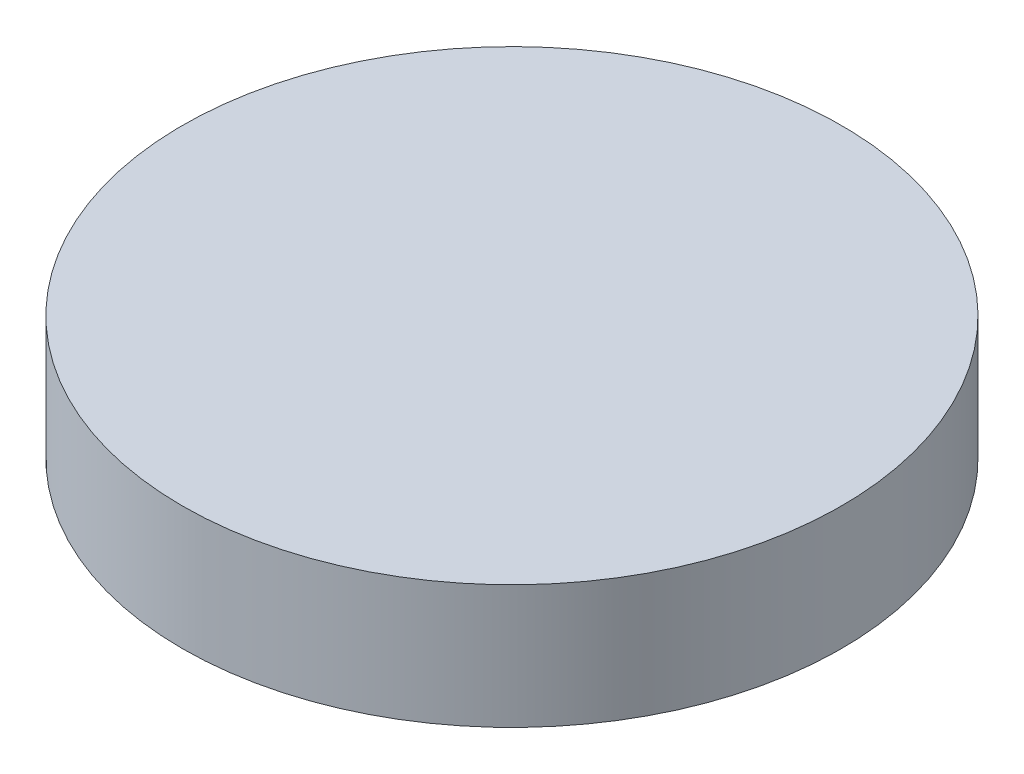
SolidWorks part; units mm, degrees
ref_plane "Front Plane" through (0, 0, 0) normal (0, 0, 1) x (1, 0, 0)
ref_plane "Top Plane" through (0, 0, 0) normal (0, 1, 0) x (1, 0, 0)
ref_plane "Right Plane" through (0, 0, 0) normal (1, 0, 0) x (0, 0, -1)
sketch "Sketch1" plane through (0, 0, 0) normal (0, 1, 0) x (1, 0, 0)
  circle A0 centre (0, 0) radius 4
  dimension "D1" = 8
extrude "Boss-Extrude1" add sketch "Sketch1" along normal blind 1.5
